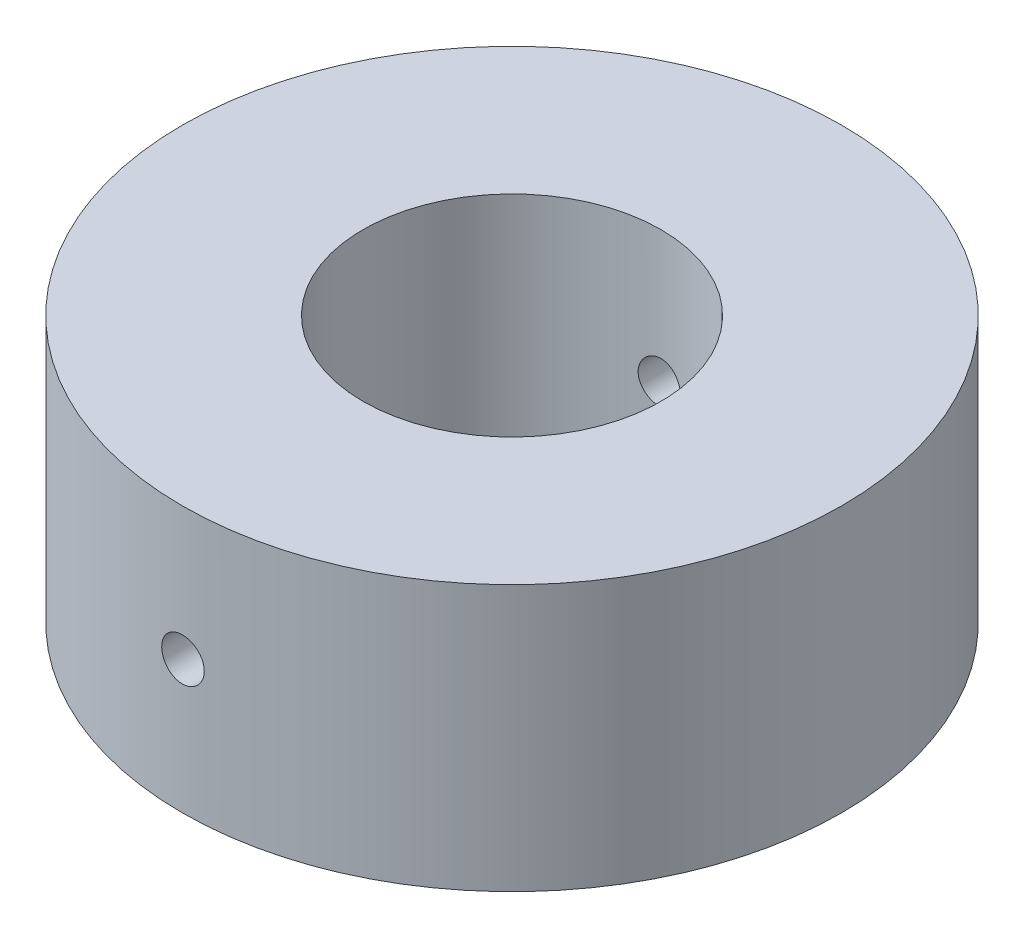
SolidWorks part; units mm, degrees
ref_plane "Front Plane" through (0, 0, 0) normal (0, 0, 1) x (1, 0, 0)
ref_plane "Top Plane" through (0, 0, 0) normal (0, 1, 0) x (1, 0, 0)
ref_plane "Right Plane" through (0, 0, 0) normal (1, 0, 0) x (0, 0, -1)
sketch "Sketch1" plane through (0, 0, 0) normal (0, 1, 0) x (1, 0, 0)
  circle A0 centre (0, 0) radius 31
  dimension "D1" = 62
extrude "Boss-Extrude1" add sketch "Sketch1" along normal mid plane 25
sketch "Sketch2" plane through (0, 0, 0) normal (0, 0, 1) x (1, 0, 0)
  line L1 (31, 12.5) -> (-31, 12.5) construction
  circle A0 centre (0, 0) radius 2
  point P2 (0, 0)
  dimension "D2" = 4
  dimension "D1" = 12.5
extrude "Cut-Extrude1" cut sketch "Sketch2" against normal through all both and the other way through all
hole_wizard "M30x2.0 Tapped Hole1" positions "Sketch5" profile "Sketch4" tap size "M30x2.0" standard "ANSI Metric"
sketch "Sketch5" plane through (0, -12.5, 0) normal (0, -1, 0) x (-1, 0, 0)
  point P0 (0, 0)
sketch "Sketch4" plane through (0, -12.5, 0) normal (1, 0, 0) x (0, 0, -1)
  line L0 (0, 0) -> (0, 33.412)
  line L1 (0, 33.412) -> (14, 25)
  line L2 (14, 25) -> (14, 1.025)
  line L3 (14, 1.025) -> (15.025, 0)
  line L5 (15.025, 0) -> (0, 0)
  line L6 (-14, 1.025) -> (-15.025, 0) construction
  line L10 (0, 33.412) -> (-14, 25) construction
  line L11 (0, -6.35) -> (0, 107.95) construction
  dimension "Tap Drill Dia." = 28
  dimension "Tap Drill Depth" = 25
  dimension "Near C'Sink Dia." = 30.05
  dimension "Near C'Sink Angle" = 90
  dimension "Drill Angle" = 118
cosmetic thread "Hole Thread1" parameters "D1"=10, "D2"=30
